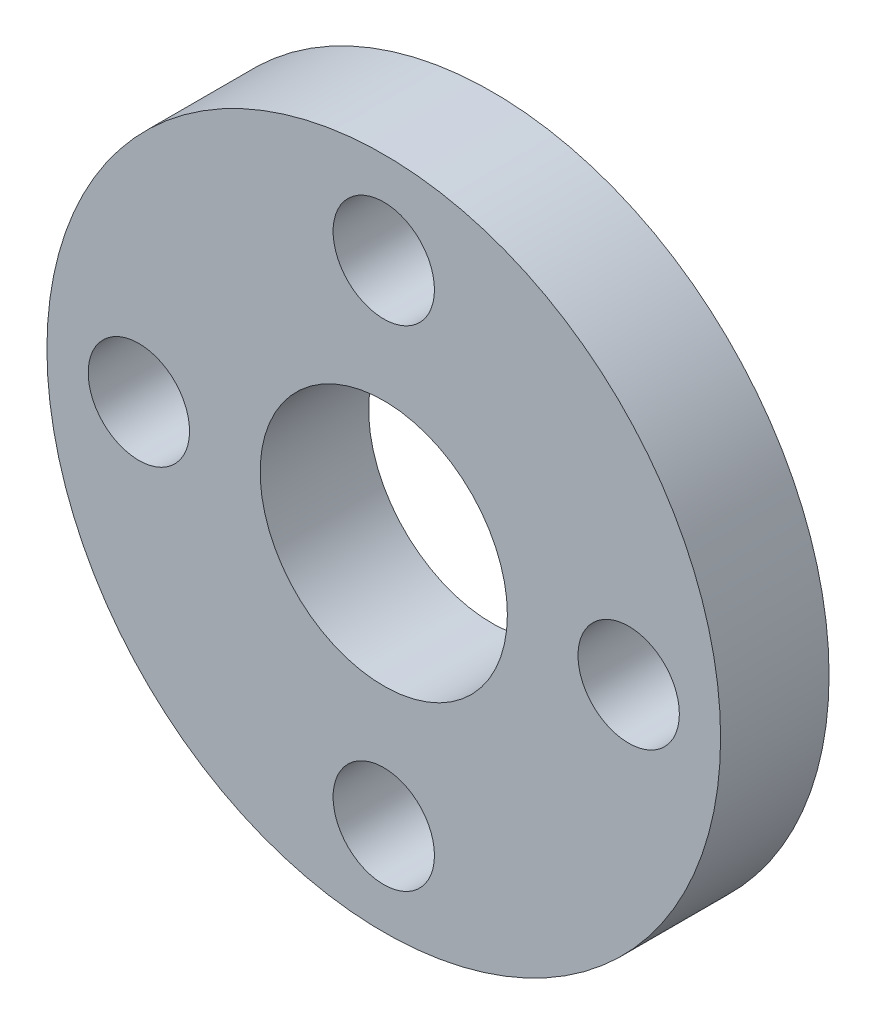
SolidWorks part; units mm, degrees
ref_plane "前视基准面" through (0, 0, 0) normal (0, 0, 1) x (1, 0, 0)
ref_plane "上视基准面" through (0, 0, 0) normal (0, 1, 0) x (1, 0, 0)
ref_plane "右视基准面" through (0, 0, 0) normal (1, 0, 0) x (0, 0, -1)
sketch "草图1" plane through (0, 0, 0) normal (0, 0, 1) x (1, 0, 0)
  circle A0 centre (0, 0) radius 10.9
  dimension "D1" = 21.8
extrude "凸台-拉伸1" add sketch "草图1" along normal blind 3.51
sketch "草图2" plane through (0, 0, 3.51) normal (0, 0, 1) x (1, 0, 0)
  circle A0 centre (0, 0) radius 7.925 construction
  circle A1 centre (7.925, 0) radius 1.64
  circle A2 centre (-7.925, 0) radius 1.64
  circle A3 centre (0, 7.925) radius 1.64
  circle A4 centre (0, -7.925) radius 1.64
  dimension "D1" = 3.28
  dimension "D2" = 3.28
  dimension "D3" = 12.57
  dimension "D4" = 3.28
  dimension "D5" = 3.28
extrude "切除-拉伸1" cut sketch "草图2" against normal blind 3.51
sketch "草图3" plane through (0, 0, 3.51) normal (0, 0, 1) x (1, 0, 0)
  circle A0 centre (0, 0) radius 4
  dimension "D1" = 8
extrude "切除-拉伸2" cut sketch "草图3" against normal blind 10
